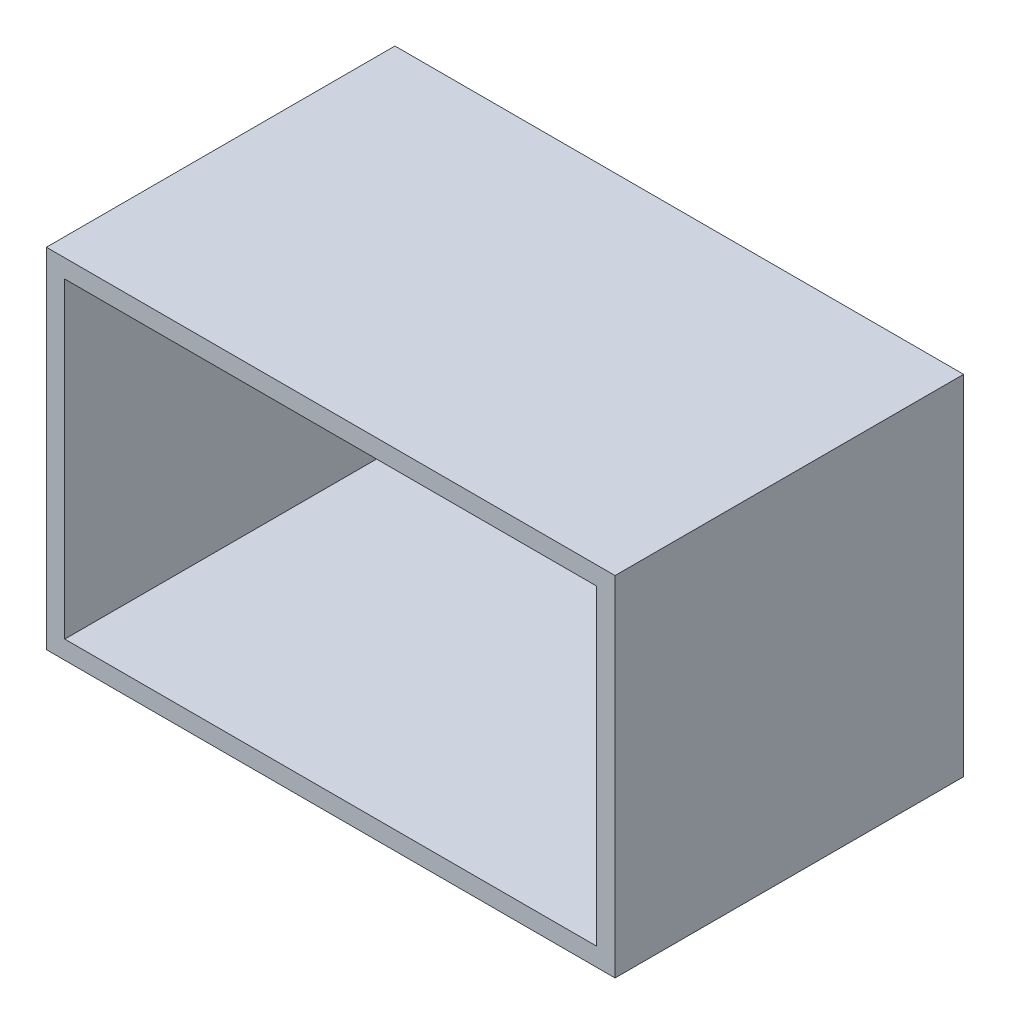
SolidWorks part; units mm, degrees
ref_plane "Front Plane" through (0, 0, 0) normal (0, 0, 1) x (1, 0, 0)
ref_plane "Top Plane" through (0, 0, 0) normal (0, 1, 0) x (1, 0, 0)
ref_plane "Right Plane" through (0, 0, 0) normal (1, 0, 0) x (0, 0, -1)
sketch "Sketch1" plane through (0, 0, 0) normal (0, 0, 1) x (1, 0, 0)
  line L1 (15.5, -9.5) -> (-15.5, -9.5)
  line L2 (15.5, -9.5) -> (15.5, 9.5)
  line L3 (15.5, 9.5) -> (-15.5, 9.5)
  line L4 (-15.5, -9.5) -> (-15.5, 9.5)
  line L5 (0, 9.5) -> (0, -9.5) construction
  line L6 (15.5, 0) -> (-15.5, 0) construction
  point P0 (0, 0)
  dimension "D1" = 19
  dimension "D2" = 31
extrude "Boss-Extrude1" add sketch "Sketch1" along normal blind 19
shell "Shell1" thickness 1
ref_plane "Plane5" through (-15.5, 9.5, 19) normal (0, 0, -1) x (-1, 0, 0)
